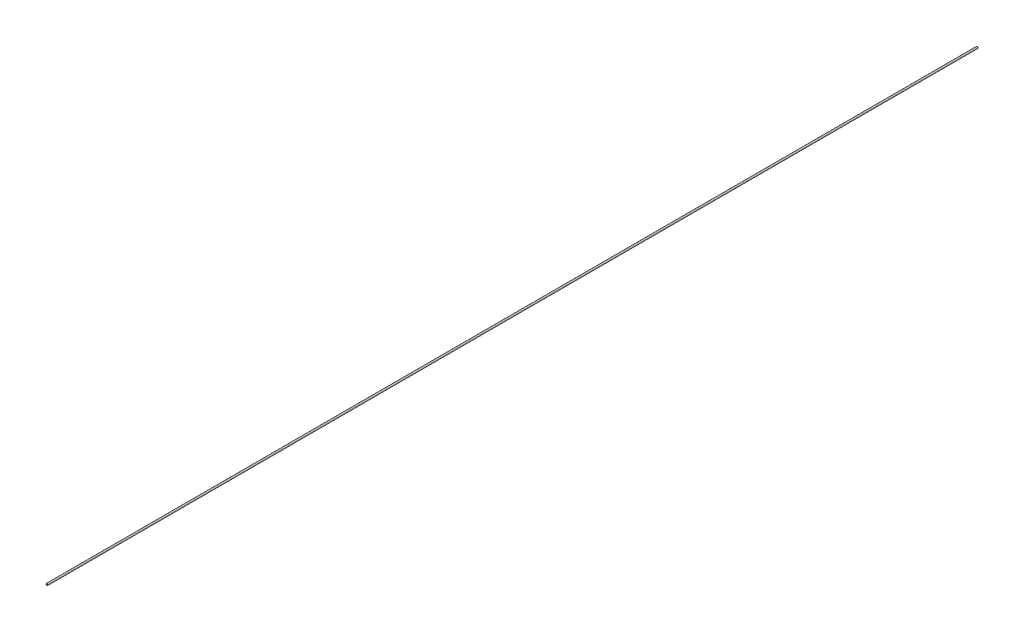
SolidWorks part; units mm, degrees
ref_plane "Plan de face" through (0, 0, 0) normal (0, 0, 1) x (1, 0, 0)
ref_plane "Plan de dessus" through (0, 0, 0) normal (0, 1, 0) x (1, 0, 0)
ref_plane "Plan de droite" through (0, 0, 0) normal (1, 0, 0) x (0, 0, -1)
sketch "Esquisse1" plane through (0, 0, 0) normal (0, 0, 1) x (1, 0, 0)
  circle A0 centre (0, 0) radius 6
  dimension "D1" = 12
extrude "Boss.-Extru.1" add sketch "Esquisse1" along normal blind 6250
fillet "Congé1" radius 2 2 edges at (6, 0, 6250) (6, 0, 0)
